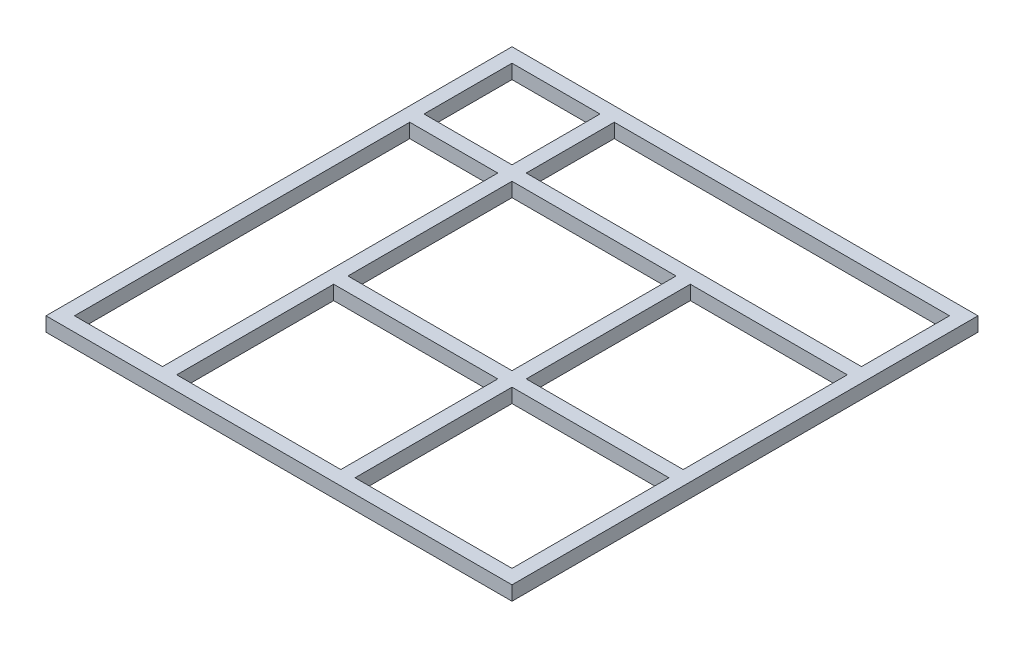
SolidWorks part; units mm, degrees
material "1023 Carbon Steel Sheet (SS)"
ref_plane "Front Plane" through (0, 0, 0) normal (0, 0, 1) x (1, 0, 0)
ref_plane "Top Plane" through (0, 0, 0) normal (0, 1, 0) x (1, 0, 0)
ref_plane "Right Plane" through (0, 0, 0) normal (1, 0, 0) x (0, 0, -1)
sketch "Sketch2" plane through (0, 0, 0) normal (0, 1, 0) x (1, 0, 0)
  line L0 (100, 413.022) -> (100, 498.9998) construction
  line L1 (0, 0) -> (426.044, 0)
  line L2 (0, 0) -> (0, 426.044)
  line L3 (0, 426.044) -> (426.044, 426.044)
  line L4 (426.044, 0) -> (426.044, 426.044)
  line L5 (13.022, 13.022) -> (93.489, 13.022)
  line L6 (13.022, 13.022) -> (13.022, 319.533)
  line L7 (13.022, 413.022) -> (93.489, 413.022)
  line L8 (413.022, 13.022) -> (413.022, 156.511)
  line L10 (93.489, 413.022) -> (93.489, 332.555)
  line L12 (106.511, 413.022) -> (106.511, 332.555)
  line L13 (13.022, 332.555) -> (93.489, 332.555)
  line L15 (13.022, 319.533) -> (93.489, 319.533)
  line L17 (13.022, 326.044) -> (413.022, 326.044) construction
  line L18 (106.511, 413.022) -> (413.022, 413.022)
  line L19 (13.022, 332.555) -> (13.022, 413.022)
  line L20 (413.022, 332.555) -> (413.022, 413.022)
  line L21 (106.511, 13.022) -> (256.511, 13.022)
  line L22 (106.511, 332.555) -> (413.022, 332.555)
  line L23 (93.489, 319.533) -> (93.489, 13.022)
  line L24 (106.511, 319.533) -> (256.511, 319.533)
  line L25 (106.511, 319.533) -> (106.511, 169.533)
  line L26 (269.533, 319.533) -> (413.022, 319.533)
  line L28 (256.511, 319.533) -> (256.511, 169.533)
  line L30 (269.533, 319.533) -> (269.533, 169.533)
  line L31 (106.511, 169.533) -> (256.511, 169.533)
  line L33 (106.511, 156.511) -> (256.511, 156.511)
  line L35 (106.511, 156.511) -> (106.511, 13.022)
  line L36 (269.533, 13.022) -> (413.022, 13.022)
  line L37 (413.022, 169.533) -> (413.022, 319.533)
  line L38 (269.533, 169.533) -> (413.022, 169.533)
  line L39 (269.533, 156.511) -> (269.533, 13.022)
  line L40 (269.533, 156.511) -> (413.022, 156.511)
  line L41 (256.511, 156.511) -> (256.511, 13.022)
  dimension "D1" = 400
  dimension "D2" = 400
  dimension "D3" = 13.022
  dimension "D4" = 13.022
  dimension "D5" = 13.022
  dimension "D6" = 13.022
  dimension "D7" = 100
  dimension "D8" = 6.511
  dimension "D9" = 13.022
  dimension "D10" = 100
  dimension "D11" = 6.511
  dimension "D12" = 6.511
  dimension "D13" = 13.022
  dimension "D14" = 13.022
  dimension "D15" = 150
  dimension "D16" = 150
extrude "Boss-Extrude1" add sketch "Sketch2" along normal blind 13.022
